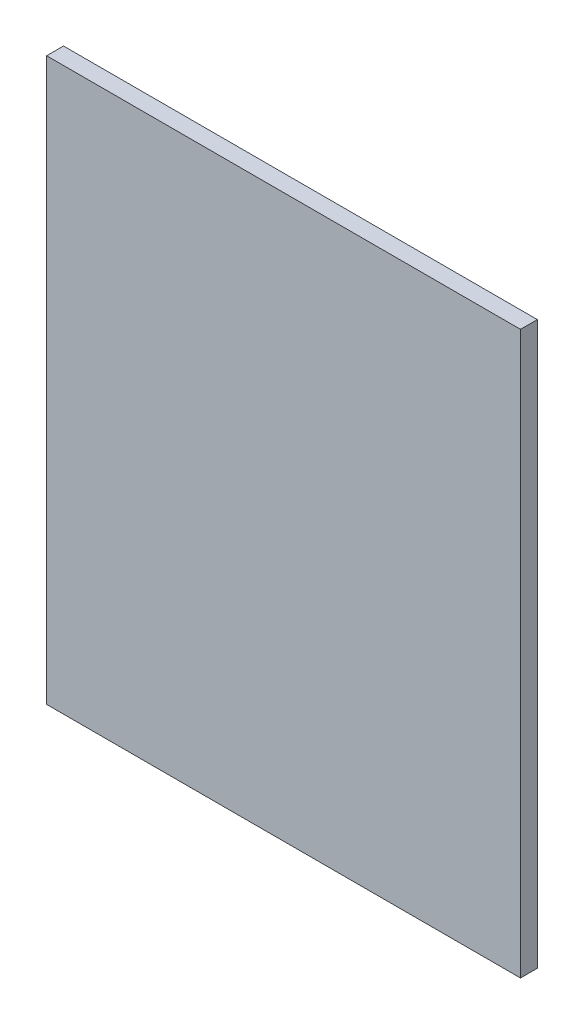
SolidWorks part; units mm, degrees
ref_plane "Plan de face" through (0, 0, 0) normal (0, 0, 1) x (1, 0, 0)
ref_plane "Plan de dessus" through (0, 0, 0) normal (0, 1, 0) x (1, 0, 0)
ref_plane "Plan de droite" through (0, 0, 0) normal (1, 0, 0) x (0, 0, -1)
sketch "Esquisse1" plane through (0, 0, 0) normal (0, 0, 1) x (1, 0, 0)
  line L1 (0, 0) -> (56.1626, 0)
  line L2 (0, 0) -> (0, 66.5806)
  line L3 (0, 66.5806) -> (56.1626, 66.5806)
  line L4 (56.1626, 0) -> (56.1626, 66.5806)
extrude "Boss.-Extru.1" add sketch "Esquisse1" along normal blind 2
